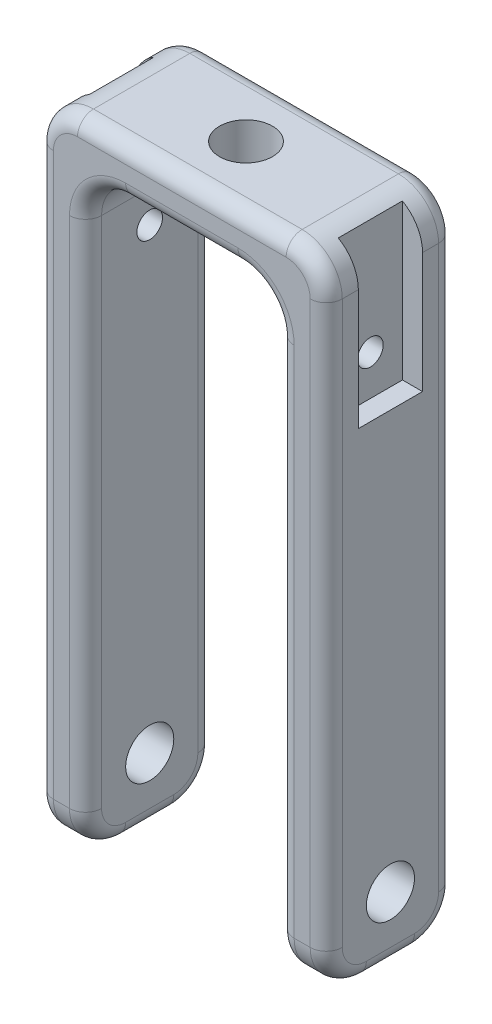
SolidWorks part; units mm, degrees
ref_plane "前视基准面" through (0, 0, 0) normal (0, 0, 1) x (1, 0, 0)
ref_plane "上视基准面" through (0, 0, 0) normal (0, 1, 0) x (1, 0, 0)
ref_plane "右视基准面" through (0, 0, 0) normal (1, 0, 0) x (0, 0, -1)
sketch "草图1" plane through (0, 0, 0) normal (0, 1, 0) x (1, 0, 0)
  line L1 (18, 8) -> (-18, 8)
  line L2 (18, 8) -> (18, -8)
  line L3 (18, -8) -> (-18, -8)
  line L4 (-18, 8) -> (-18, -8)
  line L5 (18, 8) -> (-18, -8) construction
  line L6 (18, -8) -> (-18, 8) construction
  point P0 (0, 0)
  point P6 (0, 0)
extrude "凸台-拉伸1" add sketch "草图1" against normal blind 80
sketch "草图2" plane through (0, 0, 0) normal (0, 1, 0) x (1, 0, 0)
  circle A0 centre (0, 0) radius 3.3
sketch "草图3" plane through (0, 0, 8) normal (0, 0, 1) x (1, 0, 0)
  line L0 (-18, -80) -> (18, -80) construction
  line L1 (-12, -80) -> (12, -80)
  line L2 (-12, -80) -> (-12, -6)
  line L3 (-12, -6) -> (12, -6)
  line L4 (12, -80) -> (12, -6)
extrude "切除-拉伸1" cut sketch "草图3" against normal through all
fillet "圆角1" radius 5 8 edges at (-18, 0, 0) (18, 0, 0) (12, -6, 0) (-12, -6, 0) (-15, -80, -8) (15, -80, -8) (-15, -80, 8) (15, -80, 8)
fillet "圆角2" radius 2 32 edges at (-18, -78.5355, 6.5355) (-18, -80, 0) (-18, -78.5355, -6.5355) (-18, -40, -8) (-16.5355, -1.4645, -8) (0, 0, -8) (16.5355, -1.4645, -8) (18, -40, -8) (18, -78.5355, -6.5355) (18, -80, 0) (18, -78.5355, 6.5355) (18, -40, 8) (16.5355, -1.4645, 8) (0, 0, 8) (-16.5355, -1.4645, 8) (-18, -40, 8) (-10.5355, -7.4645, 8) (0, -6, 8) (10.5355, -7.4645, 8) (12, -43, 8) (12, -78.5355, 6.5355) (12, -80, 0) (12, -78.5355, -6.5355) (12, -43, -8) (10.5355, -7.4645, -8) (0, -6, -8) (-10.5355, -7.4645, -8) (-12, -43, -8) (-12, -78.5355, -6.5355) (-12, -80, 0) (-12, -78.5355, 6.5355) (-12, -43, 8)
sketch "草图4" plane through (18, 0, 0) normal (1, 0, 0) x (0, 0, -1)
  circle A0 centre (0, -72) radius 3
extrude "切除-拉伸2" cut sketch "草图4" against normal through all
extrude "切除-拉伸3" cut sketch "草图2" against normal through all contours A0
sketch "草图5" plane through (0, 0, 0) normal (0, 1, 0) x (1, 0, 0)
  line L1 (-18, 4) -> (-15.5, 4)
  line L2 (-18, 4) -> (-18, -4)
  line L3 (-18, -4) -> (-15.5, -4)
  line L4 (-15.5, 4) -> (-15.5, -4)
  line L6 (18, 4) -> (15.5, 4)
  line L7 (18, 4) -> (18, -4)
  line L8 (18, -4) -> (15.5, -4)
  line L9 (15.5, 4) -> (15.5, -4)
  point P5 (0, 0)
  point P6 (0, 0)
  point P11 (0, 0)
  point P18 (0, 0)
  point P19 (0, 0)
  point P20 (0, 0)
  point P21 (0, 0)
  point P22 (0, 0)
  point P23 (0, 0)
  point P24 (0, 0)
extrude "切除-拉伸4" cut sketch "草图5" against normal blind 20
sketch "草图6" plane through (-15.5, 0, 0) normal (-1, 0, 0) x (0, 0, 1)
  circle A0 centre (0, -15) radius 1.6
extrude "切除-拉伸5" cut sketch "草图6" against normal through all
